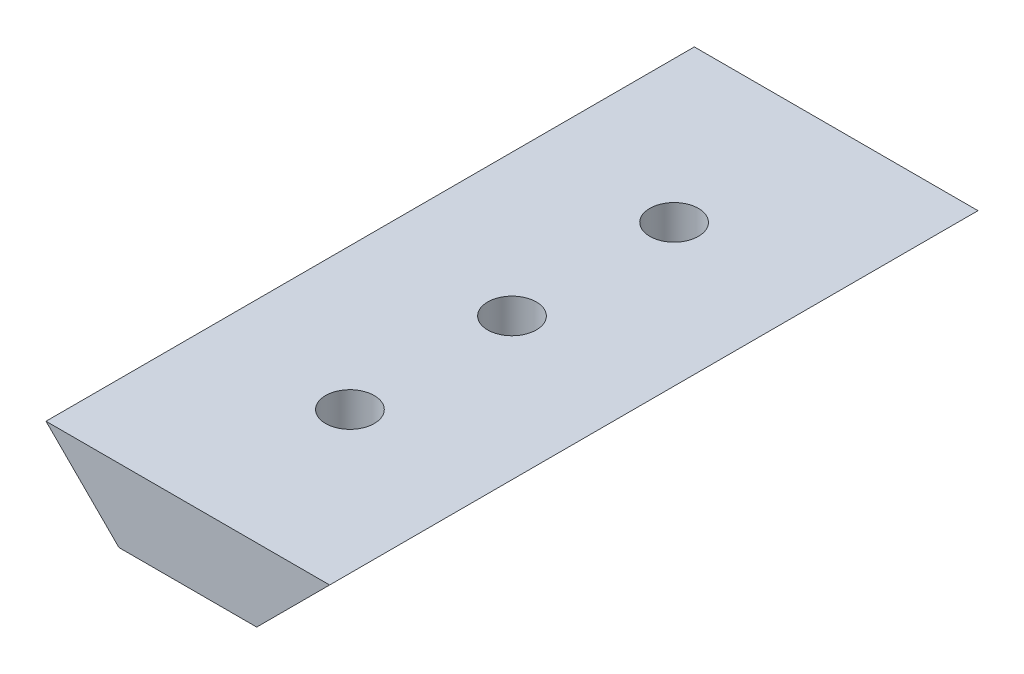
SolidWorks part; units mm, degrees
ref_plane "Plano frontal" through (0, 0, 0) normal (0, 0, 1) x (1, 0, 0)
ref_plane "Plano superior" through (0, 0, 0) normal (0, 1, 0) x (1, 0, 0)
ref_plane "Plano direito" through (0, 0, 0) normal (1, 0, 0) x (0, 0, -1)
sketch "Esboço1" plane through (0, 0, 0) normal (0, 0, 1) x (1, 0, 0)
  line L0 (-8.75, 2.25) -> (8.75, 2.25)
  line L1 (8.75, 2.25) -> (4.25, -2.25)
  line L3 (-4.25, -2.25) -> (4.25, -2.25)
  line L6 (-8.75, 2.25) -> (-4.25, -2.25)
  line L7 (0, -2.25) -> (0, 0) construction
  point P5 (0, 2.25)
  dimension "D1" = 8.75
  dimension "D2" = 4.25
  dimension "D3" = 135
extrude "Ressalto-extrusão1" add sketch "Esboço1" along normal blind 40
sketch "Esboço2" plane through (0, 2.25, 0) normal (0, 1, 0) x (1, 0, 0)
  line L0 (0, 0) -> (0, -40) construction
  line L1 (8.75, -40) -> (-8.75, -40) construction
  line L3 (8.75, 0) -> (-8.75, 0) construction
  circle A0 centre (0, -20) radius 1.5
  circle A1 centre (0, -10) radius 1.5
  circle A2 centre (0, -30) radius 1.5
  dimension "D3" = 3
  dimension "D4" = 3
  dimension "D5" = 3
  dimension "D1" = 10
  dimension "D2" = 10
extrude "Corte-extrusão1" cut sketch "Esboço2" against normal up to next
